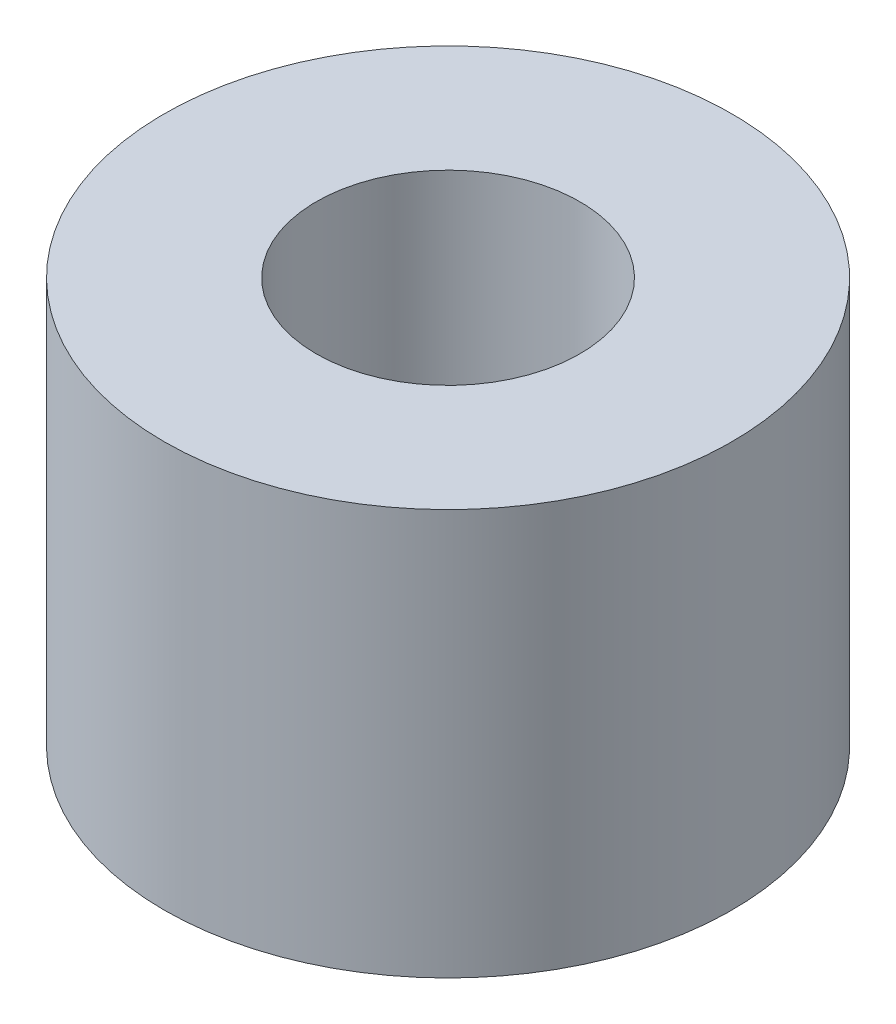
SolidWorks part; units mm, degrees
ref_plane "Front Plane" through (0, 0, 0) normal (0, 0, 1) x (1, 0, 0)
ref_plane "Top Plane" through (0, 0, 0) normal (0, 1, 0) x (1, 0, 0)
ref_plane "Right Plane" through (0, 0, 0) normal (1, 0, 0) x (0, 0, -1)
sketch "Sketch1" plane through (0, 0, 0) normal (0, 1, 0) x (1, 0, 0)
  circle A0 centre (0, 0) radius 2.6
  circle A1 centre (0, 0) radius 5.6
  dimension "D1" = 5.2
  dimension "D2" = 3
extrude "Boss-Extrude1" add sketch "Sketch1" along normal blind 8
